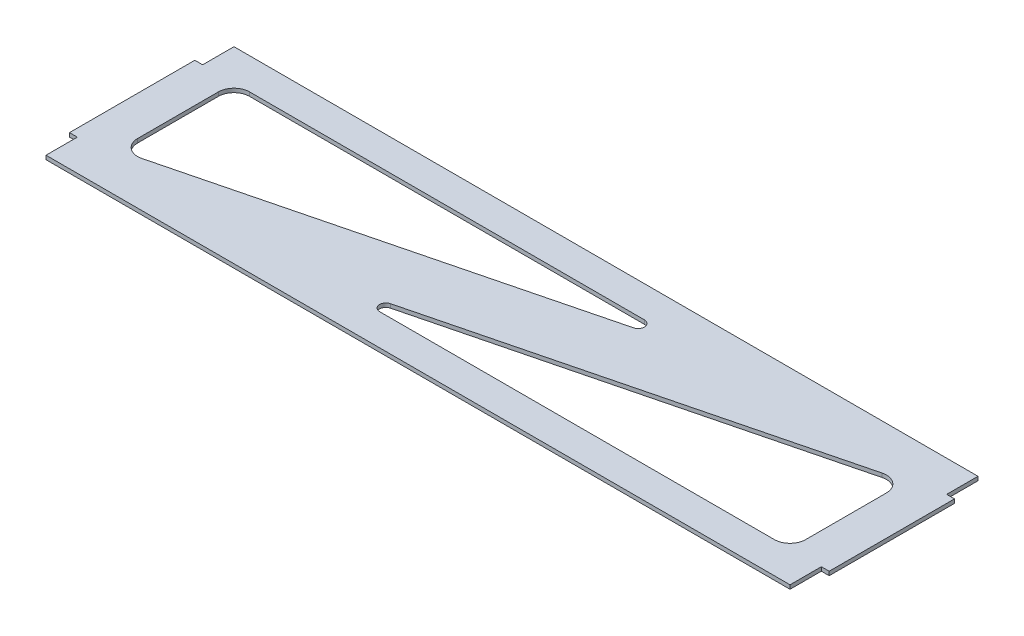
SolidWorks part; units mm, degrees
material "Balsa"
ref_plane "Front Plane" through (0, 0, 0) normal (0, 0, 1) x (1, 0, 0)
ref_plane "Top Plane" through (0, 0, 0) normal (0, 1, 0) x (1, 0, 0)
ref_plane "Right Plane" through (0, 0, 0) normal (1, 0, 0) x (0, 0, -1)
sketch "Sketch1" plane through (0, 0, 0) normal (0, 1, 0) x (1, 0, 0)
  line L0 (-150.8125, 25.4) -> (-153.9875, 25.4)
  line L1 (-150.8125, -38.1) -> (150.8125, -38.1)
  line L2 (-150.8125, -38.1) -> (-150.8125, -25.4)
  line L3 (-150.8125, 38.1) -> (150.8125, 38.1)
  line L4 (150.8125, -38.1) -> (150.8125, -25.4)
  line L5 (-150.8125, -38.1) -> (150.8125, 38.1) construction
  line L6 (-150.8125, 38.1) -> (150.8125, -38.1) construction
  line L7 (-153.9875, 25.4) -> (-153.9875, -25.4)
  line L8 (-153.9875, -25.4) -> (-150.8125, -25.4)
  line L9 (150.8125, -25.4) -> (153.9875, -25.4)
  line L10 (153.9875, -25.4) -> (153.9875, 25.4)
  line L11 (153.9875, 25.4) -> (150.8125, 25.4)
  line L12 (150.8125, 25.4) -> (150.8125, 38.1)
  line L13 (-150.8125, 25.4) -> (-150.8125, 38.1)
  point P0 (0, 0)
  point P14 (152.4, -25.4)
  point P15 (166.751, 1.397)
  dimension "D1" = 301.625
  dimension "D2" = 76.2
  dimension "D3" = 3.175
  dimension "D4" = 12.7
  dimension "D5" = 12.7
  dimension "D6" = 12.7
  dimension "D7" = 12.7
  dimension "D8" = 3.175
extrude "Boss-Extrude1" add sketch "Sketch1" along normal blind 1.5875
sketch "Sketch2" plane through (0, 1.5875, 0) normal (0, 1, 0) x (1, 0, 0)
  line L0 (-1000, 0) -> (49000, 0) construction
  line L1 (0, -1000) -> (0, 49000) construction
  line L2 (-150.8125, 38.1) -> (150.8125, 38.1) construction
  line L4 (-138.1125, 19.05) -> (-138.1125, -13.6389)
  line L5 (-130.2072, -19.7954) -> (28.8894, 20.3974)
  line L6 (28.2672, 25.4) -> (-131.7625, 25.4)
  line L9 (-150.8125, 25.4) -> (-150.8125, 38.1) construction
  line L10 (-28.2672, -25.4) -> (131.7625, -25.4)
  line L11 (130.2072, 19.7954) -> (-28.8894, -20.3974)
  line L12 (-154.5735, -39.0502) -> (48321.6324, 12207.5703) construction
  line L13 (138.1125, -19.05) -> (138.1125, 13.6389)
  line L14 (-150.8125, -38.1) -> (150.8125, -38.1) construction
  line L15 (150.8125, 25.4) -> (150.8125, 38.1) construction
  arc A0 (-138.1125, -13.6389) -> (-130.2072, -19.7954) centre (-131.7625, -13.6389) ccw
  arc A1 (-138.1125, 19.05) -> (-131.7625, 25.4) centre (-131.7625, 19.05) cw
  arc A2 (28.8894, 20.3974) -> (28.2672, 25.4) centre (28.2672, 22.86) ccw
  arc A6 (-28.8894, -20.3974) -> (-28.2672, -25.4) centre (-28.2672, -22.86) ccw
  arc A7 (138.1125, -19.05) -> (131.7625, -25.4) centre (131.7625, -19.05) cw
  arc A8 (138.1125, 13.6389) -> (130.2072, 19.7954) centre (131.7625, 13.6389) ccw
  point P22 (48.6914, 25.4)
  dimension "D4" = 6.35
  dimension "D6" = 2.54
  dimension "D9" = 6.35
  dimension "D10" = 6.35
  dimension "D11" = 2.54
  dimension "D1" = 12.7
  dimension "D2" = 12.7
  dimension "D3" = 12.7
  dimension "D5" = 12.7
  dimension "D7" = 12.7
  dimension "D8" = 12.7
extrude "Cut-Extrude1" cut sketch "Sketch2" against normal through all
